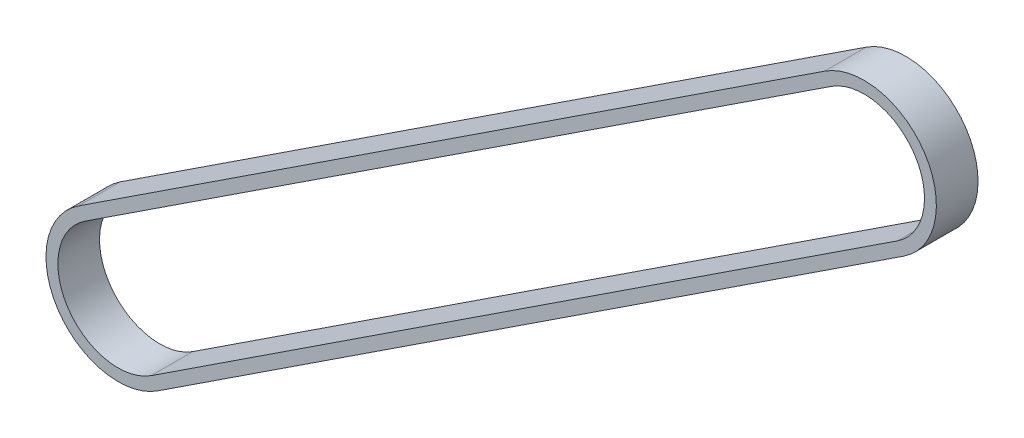
SolidWorks part; units mm, degrees
material "BUTYL"
ref_plane "前视基准面" through (0, 0, 0) normal (0, 0, 1) x (1, 0, 0)
ref_plane "上视基准面" through (0, 0, 0) normal (0, 1, 0) x (1, 0, 0)
ref_plane "右视基准面" through (0, 0, 0) normal (1, 0, 0) x (0, 0, -1)
sketch "草图2" plane through (0, 0, 0) normal (0, 0, 1) x (1, 0, 0)
  line L0 (0, 0) -> (1, 0) construction
  line L1 (0, 0) -> (0, 1) construction
  line L2 (42.6327, -24.7811) -> (168.032, 57.5293)
  line L3 (179.1439, 40.6004) -> (53.7446, -41.71)
  arc A0 (53.7446, -41.71) -> (42.6327, -24.7811) centre (48.1886, -33.2456) cw
  arc A1 (168.032, 57.5293) -> (179.1439, 40.6004) centre (173.588, 49.0648) cw
extrude "拉伸-薄壁1" add sketch "草图2" along normal mid plane 7 thin thin type one direction wall 2
